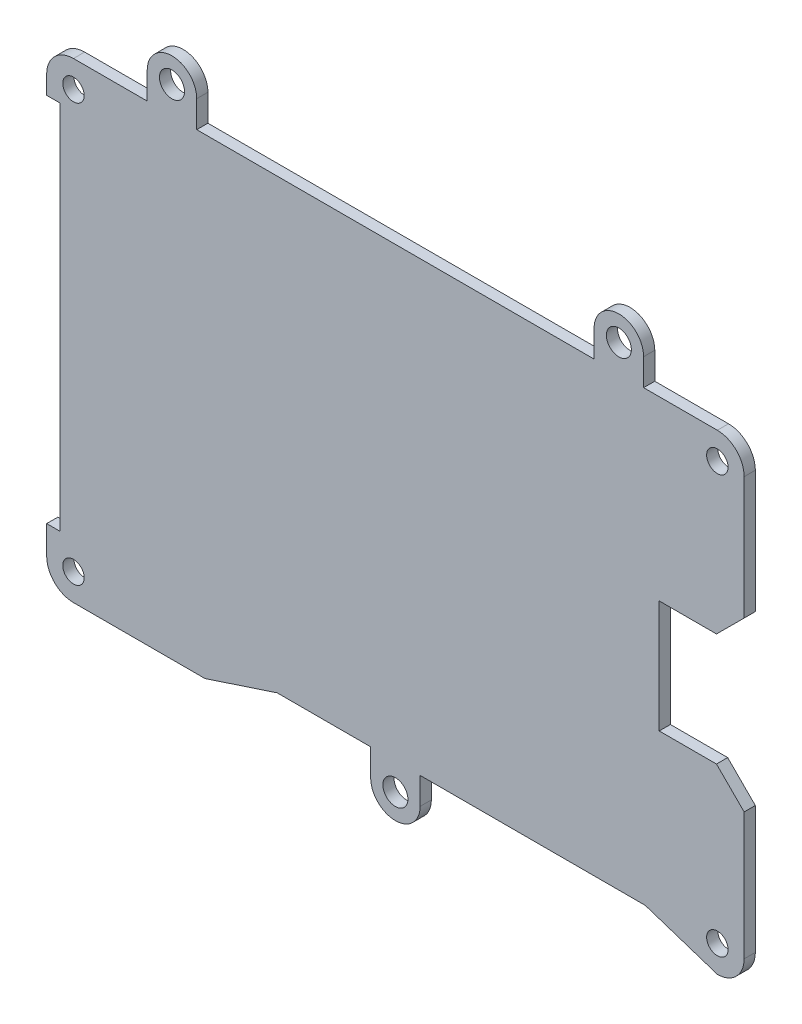
SolidWorks part; units mm, degrees
ref_plane "Front Plane" through (0, 0, 0) normal (0, 0, 1) x (1, 0, 0)
ref_plane "Top Plane" through (0, 0, 0) normal (0, 1, 0) x (1, 0, 0)
ref_plane "Right Plane" through (0, 0, 0) normal (1, 0, 0) x (0, 0, -1)
sketch "Sketch1" plane through (0, 0, 0) normal (0, 0, 1) x (1, 0, 0)
  line L0 (-301.9473, 111.7465) -> (-305.8779, 115.6771) construction
  line L1 (-305.8779, 115.6771) -> (-316.1078, 115.6771) construction
  line L2 (-316.1078, 115.6771) -> (-316.1078, 128.8851) construction
  line L3 (-316.1078, 128.8851) -> (-305.8779, 128.8851) construction
  line L4 (-305.8779, 128.8851) -> (-301.9473, 132.8157) construction
  line L5 (-301.9473, 132.8157) -> (-301.9473, 150.9704) construction
  line L6 (-305.7573, 154.7804) -> (-397.2471, 154.7804) construction
  line L7 (-401.0571, 150.9566) -> (-401.0571, 148.341) construction
  line L8 (-401.0571, 148.341) -> (-399.1521, 148.341) construction
  line L9 (-399.1521, 148.341) -> (-399.1521, 95.6449) construction
  line L10 (-399.1521, 95.6449) -> (-401.0571, 95.6449) construction
  line L11 (-401.0571, 95.6449) -> (-401.0571, 91.6593) construction
  line L12 (-397.2472, 87.8217) -> (-378.5565, 87.8217) construction
  line L13 (-378.5565, 87.8217) -> (-368.3165, 91.1883) construction
  line L14 (-368.3165, 91.1883) -> (-315.9973, 91.1883) construction
  line L15 (-315.9973, 91.1883) -> (-305.7573, 87.8217) construction
  line L16 (-301.9473, 91.6317) -> (-301.9473, 111.7465) construction
  line L17 (-301.9473, 111.7465) -> (-305.8779, 115.6771)
  line L18 (-305.8779, 115.6771) -> (-316.1078, 115.6771)
  line L19 (-316.1078, 115.6771) -> (-316.1078, 128.8851)
  line L20 (-316.1078, 128.8851) -> (-305.8779, 128.8851)
  line L21 (-305.8779, 128.8851) -> (-301.9473, 132.8157)
  line L22 (-301.9473, 132.8157) -> (-301.9473, 150.9704)
  line L23 (-305.7573, 154.7804) -> (-397.2471, 154.7804)
  line L24 (-401.0571, 150.9566) -> (-401.0571, 148.341)
  line L25 (-401.0571, 148.341) -> (-399.1521, 148.341)
  line L26 (-399.1521, 148.341) -> (-399.1521, 95.6449)
  line L27 (-399.1521, 95.6449) -> (-401.0571, 95.6449)
  line L28 (-401.0571, 95.6449) -> (-401.0571, 91.6593)
  line L29 (-397.2472, 87.8217) -> (-378.5565, 87.8217)
  line L30 (-378.5565, 87.8217) -> (-368.3165, 91.1883)
  line L31 (-368.3165, 91.1883) -> (-315.9973, 91.1883)
  line L32 (-315.9973, 91.1883) -> (-305.7573, 87.8217)
  line L33 (-301.9473, 91.6317) -> (-301.9473, 111.7465)
  circle A0 centre (-305.7573, 91.6317) radius 1.3559 construction
  circle A1 centre (-305.7573, 150.9704) radius 1.3559 construction
  circle A2 centre (-397.2471, 150.9704) radius 1.3559 construction
  circle A3 centre (-397.2472, 91.6317) radius 1.3559 construction
  circle A4 centre (-305.7573, 91.6317) radius 1.3559
  circle A5 centre (-305.7573, 150.9704) radius 1.3559
  circle A6 centre (-397.2471, 150.9704) radius 1.3559
  circle A7 centre (-397.2472, 91.6317) radius 1.3559
  arc A8 (-301.9473, 150.9704) -> (-305.7573, 154.7804) centre (-305.7573, 150.9704) ccw construction
  arc A9 (-397.2471, 154.7804) -> (-401.0571, 150.9566) centre (-397.2471, 150.9704) ccw construction
  arc A10 (-401.0571, 91.6593) -> (-397.2472, 87.8217) centre (-397.2472, 91.6317) ccw construction
  arc A11 (-305.7573, 87.8217) -> (-301.9473, 91.6317) centre (-305.7573, 91.6317) ccw construction
  arc A12 (-301.9473, 150.9704) -> (-305.7573, 154.7804) centre (-305.7573, 150.9704) ccw
  arc A13 (-397.2471, 154.7804) -> (-401.0571, 150.9566) centre (-397.2471, 150.9704) ccw
  arc A14 (-401.0571, 91.6593) -> (-397.2472, 87.8217) centre (-397.2472, 91.6317) ccw
  arc A15 (-305.7573, 87.8217) -> (-301.9473, 91.6317) centre (-305.7573, 91.6317) ccw
extrude "Boss-Extrude1" add sketch "Sketch1" along normal blind 1.5875
sketch "Sketch2" plane through (0, 0, 1.5875) normal (0, 0, 1) x (1, 0, 0)
  line L0 (-351.5022, 121.301) -> (-351.5022, 159.401) construction
  line L1 (-301.9473, 150.9704) -> (-301.9473, 91.6317) construction
  line L2 (-401.0571, 121.301) -> (-301.9473, 121.301) construction
  line L3 (-351.5022, 83.201) -> (-351.5022, 159.401) construction
  line L4 (-361.0272, 83.201) -> (-361.0272, 159.401)
  line L5 (-341.9772, 83.201) -> (-341.9772, 159.401)
  line L6 (-361.0272, 154.7804) -> (-341.9772, 154.7804)
  line L7 (-305.7573, 154.7804) -> (-397.2471, 154.7804) construction
  line L8 (-361.0272, 91.6317) -> (-341.9772, 91.6317)
  circle A0 centre (-351.5022, 159.401) radius 3.175
  arc A1 (-361.0272, 83.201) -> (-341.9772, 83.201) centre (-351.5022, 83.201) ccw
  arc A2 (-341.9772, 159.401) -> (-361.0272, 159.401) centre (-351.5022, 159.401) ccw
  circle A3 centre (-351.5022, 83.201) radius 3.175
  point P13 (-351.5022, 121.301)
  line M11 (-305.7573, 154.7804) -> (-397.2471, 154.7804)
  line M21 (-368.3165, 91.1883) -> (-315.9973, 91.1883)
  dimension "D1" = 6.35
  dimension "D2" = 38.1
  dimension "D3" = 19.05
extrude "Boss-Extrude2" [suppressed] add sketch "Sketch2" against normal blind 1.5875 contours L5 A2 L4 A0 M11 | L4 A1 L5 A3 M21
sketch "Sketch3" plane through (0, 0, 1.5875) normal (0, 0, 1) x (1, 0, 0)
  circle A0 centre (-397.2471, 150.9704) radius 1.524
  circle A1 centre (-305.7573, 150.9704) radius 1.524
  circle A2 centre (-305.7573, 91.6317) radius 1.524
  circle A3 centre (-397.2472, 91.6317) radius 1.524
  dimension "D1" = 3.048
extrude "Cut-Extrude1" cut sketch "Sketch3" against normal through all
sketch "Sketch4" plane through (0, 0, 1.5875) normal (0, 0, 1) x (1, 0, 0)
  line L0 (-301.9473, 133.571) -> (-305.8779, 129.6471)
  line L2 (-301.9473, 132.8157) -> (-301.9473, 150.9704) construction
  line L3 (-305.8779, 129.6471) -> (-314.0123, 129.6471)
  line L4 (-314.0123, 129.6471) -> (-314.0123, 113.6451)
  line L5 (-314.0123, 113.6451) -> (-305.8779, 113.6451)
  line L7 (-305.8779, 113.6451) -> (-301.9473, 109.7145)
  line L11 (-301.9473, 91.6317) -> (-301.9473, 111.7465) construction
  line L12 (-301.9473, 109.7145) -> (-301.9473, 133.571)
  dimension "D1" = 18.0828
  dimension "D2" = 16.002
  dimension "D3" = 8.1344
  dimension "D4" = 3.9306
  dimension "D5" = 23.8566
  dimension "D6" = 8.1344
  dimension "D7" = 5.5588
sketch "Sketch5" plane through (0, 0, 1.5875) normal (0, 0, 1) x (1, 0, 0)
  line L0 (-316.1078, 128.8851) -> (-305.8779, 128.8851) construction
  line L1 (-314.0123, 128.8851) -> (-316.1078, 128.8851)
  line L2 (-314.0123, 128.8851) -> (-314.0123, 115.6771)
  line L3 (-314.0123, 115.6771) -> (-316.1078, 115.6771)
  line L4 (-316.1078, 128.8851) -> (-316.1078, 115.6771)
  line L5 (-301.9473, 91.6317) -> (-301.9473, 111.7465) construction
  dimension "D1" = 12.065
extrude "Boss-Extrude3" add sketch "Sketch5" against normal up to vertex (1.5875 mm away) up to point (-316.1078, 128.8851, 0)
extrude "Cut-Extrude2" cut sketch "Sketch4" against normal through all
sketch "Sketch6" plane through (0, 0, 0) normal (0, 0, -1) x (-1, 0, 0)
  line L0 (351.5022, 154.7804) -> (351.5022, 91.1883) construction
  line L1 (368.3165, 91.1883) -> (315.9973, 91.1883) construction
  line L5 (305.7573, 154.7804) -> (397.2471, 154.7804) construction
  line L6 (379.7343, 158.5904) -> (379.7343, 154.7804)
  line L7 (379.7343, 154.7804) -> (386.7701, 154.7804)
  line L8 (386.7701, 154.7804) -> (386.7701, 158.5904)
  line L9 (347.9843, 87.3783) -> (347.9843, 91.1883)
  line L10 (347.9843, 91.1883) -> (355.0201, 91.1883)
  line L11 (355.0201, 91.1883) -> (355.0201, 87.3783)
  line L13 (316.2343, 154.7804) -> (316.2343, 158.5904)
  line L14 (323.2701, 154.7804) -> (316.2343, 154.7804)
  line L15 (323.2701, 158.5904) -> (323.2701, 154.7804)
  circle A0 centre (351.5022, 87.3783) radius 1.778
  circle A1 centre (351.5022, 87.3783) radius 3.5179
  circle A2 centre (383.2522, 158.5904) radius 3.5179
  circle A3 centre (383.2522, 158.5904) radius 1.778
  circle A4 centre (319.7522, 158.5904) radius 1.778
  circle A5 centre (319.7522, 158.5904) radius 3.5179
  dimension "D1" = 7.0358
  dimension "D2" = 7.0358
  dimension "D6" = 3.556
  dimension "D3" = 3.81
  dimension "D4" = 63.5
  dimension "D5" = 3.81
extrude "Boss-Extrude4" add sketch "Sketch6" against normal up to vertex (1.5875 mm away)
